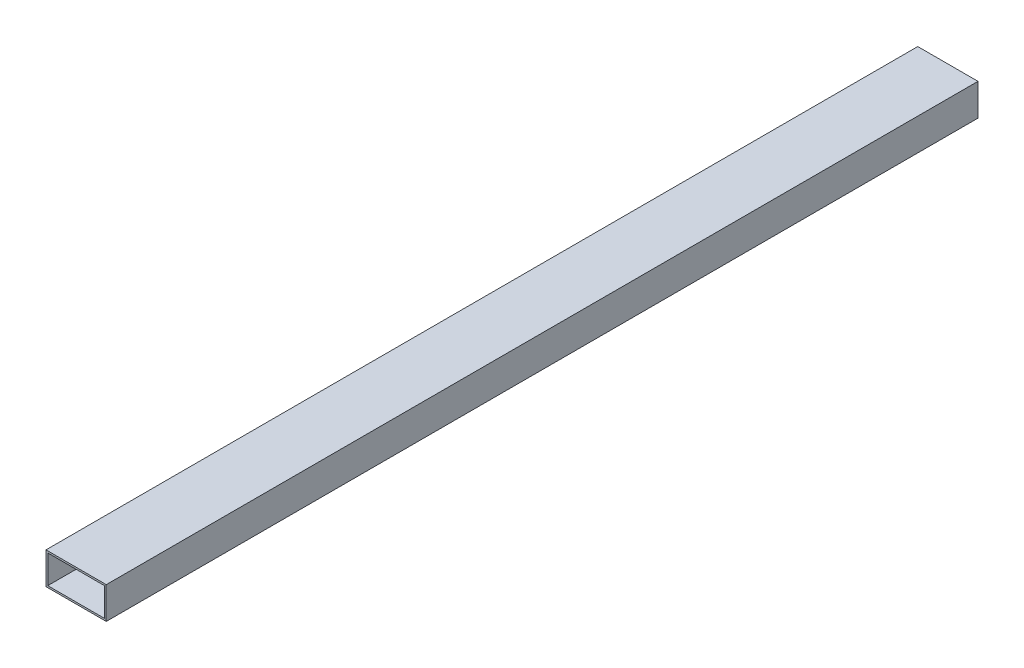
SolidWorks part; units mm, degrees
ref_plane "Front Plane" through (0, 0, 0) normal (0, 0, 1) x (1, 0, 0)
ref_plane "Top Plane" through (0, 0, 0) normal (0, 1, 0) x (1, 0, 0)
ref_plane "Right Plane" through (0, 0, 0) normal (1, 0, 0) x (0, 0, -1)
sketch "Sketch1" plane through (0, 0, 0) normal (0, 0, 1) x (1, 0, 0)
  line L1 (0, 0) -> (-50.8, 0)
  line L2 (0, 0) -> (0, -25.4)
  line L3 (0, -25.4) -> (-50.8, -25.4)
  line L4 (-50.8, 0) -> (-50.8, -25.4)
  dimension "D1" = 50.8
  dimension "D2" = 25.4
extrude "Extrude-Thin1" add sketch "Sketch1" along normal blind 781.05 thin
